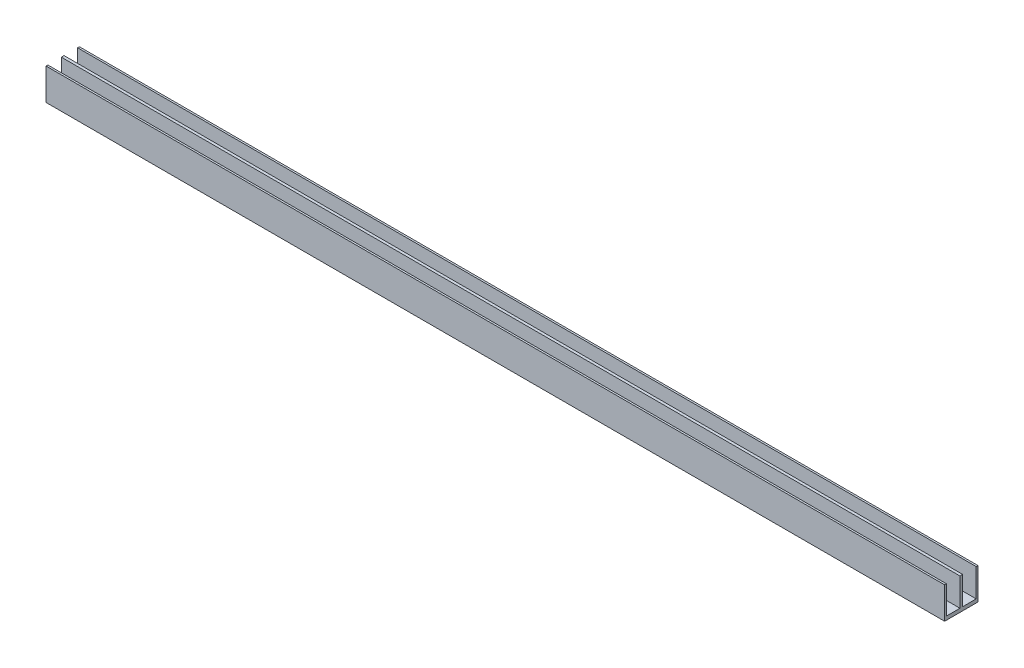
SolidWorks part; units mm, degrees
material "1060 Alloy"
ref_plane "Front Plane" through (0, 0, 0) normal (0, 0, 1) x (1, 0, 0)
ref_plane "Top Plane" through (0, 0, 0) normal (0, 1, 0) x (1, 0, 0)
ref_plane "Right Plane" through (0, 0, 0) normal (1, 0, 0) x (0, 0, -1)
sketch "Sketch2" plane through (0, 0, 0) normal (0, 1, 0) x (1, 0, 0)
  line L1 (-535.124, 207.6446) -> (464.876, 207.6446)
  line L2 (-535.124, 207.6446) -> (-535.124, 170.6446)
  line L3 (-535.124, 170.6446) -> (464.876, 170.6446)
  line L4 (464.876, 207.6446) -> (464.876, 170.6446)
  dimension "D1" = 1000
  dimension "D2" = 37
extrude "Boss-Extrude1" add sketch "Sketch2" along normal blind 35
sketch "Sketch3" plane through (0, 35, 0) normal (0, 1, 0) x (1, 0, 0)
  line L0 (464.876, 207.6446) -> (-535.124, 207.6446) construction
  line L1 (464.876, 205.6446) -> (-535.124, 205.6446)
  line L2 (464.876, 205.6446) -> (464.876, 190.6446)
  line L3 (464.876, 190.6446) -> (-535.124, 190.6446)
  line L4 (-535.124, 205.6446) -> (-535.124, 190.6446)
  line L5 (464.876, 187.6446) -> (-535.124, 187.6446)
  line L6 (464.876, 187.6446) -> (464.876, 172.6446)
  line L7 (464.876, 172.6446) -> (-535.124, 172.6446)
  line L8 (-535.124, 187.6446) -> (-535.124, 172.6446)
  line L9 (-535.124, 170.6446) -> (464.876, 170.6446) construction
  line L10 (-535.124, 207.6446) -> (-535.124, 170.6446) construction
  line L11 (464.876, 170.6446) -> (464.876, 207.6446) construction
  dimension "D1" = 2
  dimension "D2" = 2
  dimension "D3" = 3
  dimension "D4" = 15
  dimension "D5" = 0
  dimension "D6" = 0
  dimension "D7" = 0
  dimension "D8" = 0
extrude "Cut-Extrude1" cut sketch "Sketch3" against normal blind 31
sketch "Sketch4" plane through (0, 0, -207.6446) normal (0, 0, -1) x (-1, 0, 0)
  line L0 (-464.876, 0) -> (535.124, 0) construction
  line L1 (531.124, 0) -> (535.124, 0)
  line L2 (531.124, 0) -> (531.124, 35)
  line L3 (531.124, 35) -> (535.124, 35)
  line L4 (535.124, 0) -> (535.124, 35)
  line L5 (-464.876, 35) -> (535.124, 35) construction
  line L6 (535.124, 35) -> (535.124, 0) construction
  point P4 (533.124, 0)
  dimension "D1" = 0
  dimension "D2" = 0
  dimension "D3" = 0
  dimension "D4" = 4
extrude "Cut-Extrude2" cut sketch "Sketch4" against normal blind 190
